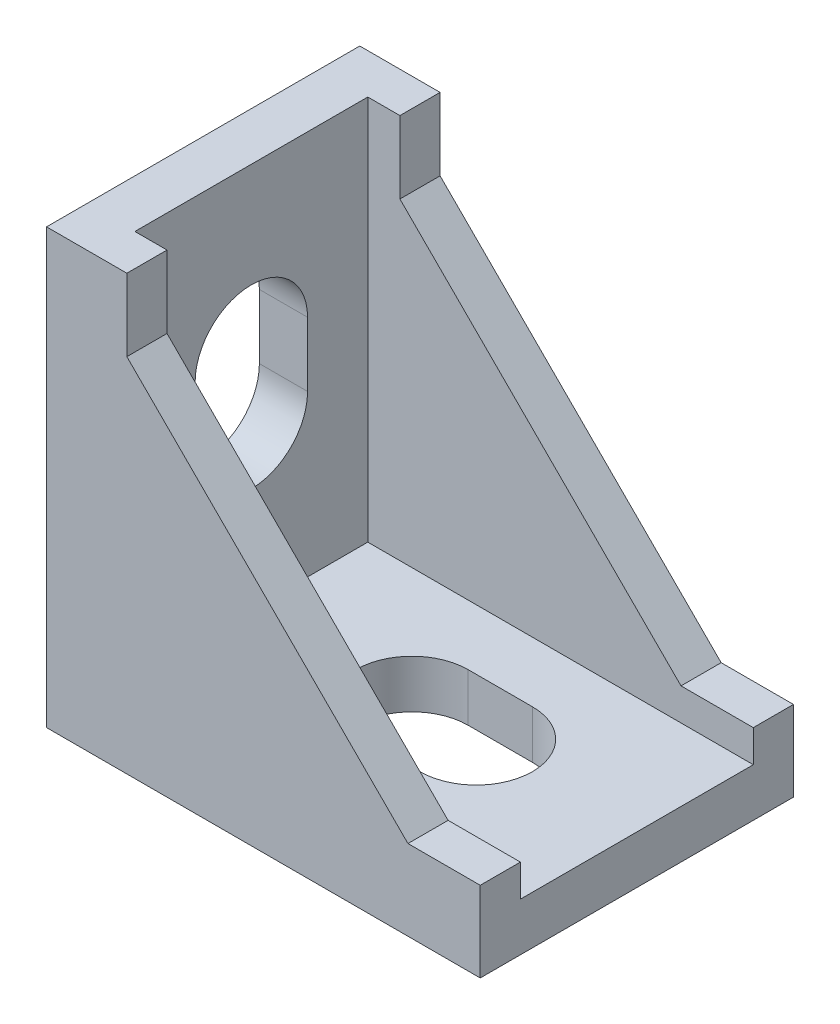
SolidWorks part; units mm, degrees
ref_plane "Front Plane" through (0, 0, 0) normal (0, 0, 1) x (1, 0, 0)
ref_plane "Top Plane" through (0, 0, 0) normal (0, 1, 0) x (1, 0, 0)
ref_plane "Right Plane" through (0, 0, 0) normal (1, 0, 0) x (0, 0, -1)
sketch "Sketch1" plane through (0, 0, 0) normal (0, 0, 1) x (1, 0, 0)
  line L0 (0, 0) -> (0, 27)
  line L1 (0, 27) -> (5, 27)
  line L2 (5, 27) -> (5, 22.5)
  line L3 (5, 22.5) -> (22.5, 5)
  line L4 (22.5, 5) -> (27, 5)
  line L5 (27, 5) -> (27, 0)
  line L6 (27, 0) -> (0, 0)
  dimension "D1" = 27
  dimension "D2" = 27
  dimension "D3" = 5
  dimension "D4" = 5
  dimension "D5" = 4.5
  dimension "D6" = 4.5
extrude "Boss-Extrude1" add sketch "Sketch1" along normal blind 19.5
ref_plane "Plane1" through (0, 0, 17) normal (0, 0, 1) x (1, 0, 0)
sketch "Sketch2" plane through (0, 0, 17) normal (0, 0, 1) x (1, 0, 0)
  line L2 (5, 27) -> (0, 27) construction
  line L5 (3, 27) -> (5, 27)
  line L6 (5, 27) -> (5, 22.5)
  line L7 (5, 22.5) -> (22.5, 5)
  line L8 (22.5, 5) -> (27, 5)
  line L11 (3, 27) -> (3, 3)
  line L12 (3, 3) -> (27, 3)
  line L13 (27, 0) -> (27, 5) construction
  line L14 (27, 3) -> (27, 5)
  line L15 (0, 27) -> (0, 0) construction
  line L16 (0, 0) -> (27, 0) construction
  dimension "D1" = 3
  dimension "D2" = 3
extrude "Cut-Extrude2" cut sketch "Sketch2" against normal blind 14.5
sketch "Sketch3" plane through (0, 3, 0) normal (0, 1, 0) x (1, 0, 0)
  line L0 (15, -2.5) -> (15, -17) construction
  line L1 (3, -2.5) -> (27, -2.5) construction
  line L2 (-14.85, -17) -> (14.85, -17) construction
  line L3 (3, -9.75) -> (27, -9.75) construction
  line L4 (3, -2.5) -> (3, -17) construction
  line L5 (27, -2.5) -> (27, -17) construction
  line L6 (13, -9.75) -> (17, -9.75) construction
  line L7 (13, -6.25) -> (17, -6.25)
  line L8 (13, -13.25) -> (17, -13.25)
  line L9 (3, -2.5) -> (3, -17) construction
  arc A0 (13, -6.25) -> (13, -13.25) centre (13, -9.75) ccw
  arc A1 (17, -13.25) -> (17, -6.25) centre (17, -9.75) ccw
  point P14 (15, -9.75)
  point P19 (9.5, -9.75)
  point P20 (20.5, -9.75)
  point P24 (15, -9.75)
  dimension "D2" = 11
  dimension "D1" = 7
extrude "Cut-Extrude3" cut sketch "Sketch3" against normal through all
sketch "Sketch4" plane through (3, 0, 0) normal (1, 0, 0) x (0, 0, -1)
  line L0 (-9.75, 3) -> (-9.75, 27) construction
  line L1 (-2.5, 3) -> (-17, 3) construction
  line L2 (-2.5, 27) -> (-17, 27) construction
  line L3 (-2.5, 15) -> (-17, 15) construction
  line L4 (-2.5, 27) -> (-2.5, 3) construction
  line L5 (-17, 14.85) -> (-17, -14.85) construction
  line L6 (-9.75, 13) -> (-9.75, 17) construction
  line L7 (-13.25, 13) -> (-13.25, 17)
  line L8 (-6.25, 13) -> (-6.25, 17)
  arc A0 (-13.25, 13) -> (-6.25, 13) centre (-9.75, 13) ccw
  arc A1 (-6.25, 17) -> (-13.25, 17) centre (-9.75, 17) ccw
  point P14 (-9.75, 15)
  point P19 (-9.75, 9.5)
  point P20 (-9.75, 20.5)
  dimension "D1" = 7
  dimension "D2" = 11
extrude "Cut-Extrude4" cut sketch "Sketch4" against normal through all
sketch "Sketch5" plane through (0, 0, 0) normal (-1, 0, 0) x (0, 0, 1)
  line L0 (6.25, 17) -> (13.25, 13) construction
  line L1 (6.25, 13) -> (13.25, 17) construction
  circle A0 centre (9.75, 15) radius 3.5
sketch "Sketch6" plane through (0, 0, 0) normal (0, -1, 0) x (1, 0, 0)
  line L0 (13, 13.25) -> (17, 6.25) construction
  line L1 (17, 13.25) -> (13, 6.25) construction
  arc A0 (17, 6.25) -> (17, 13.25) centre (17, 9.75) ccw construction
  circle A1 centre (15, 9.75) radius 3.5
equation "\"19.5.00mm\"=195"
